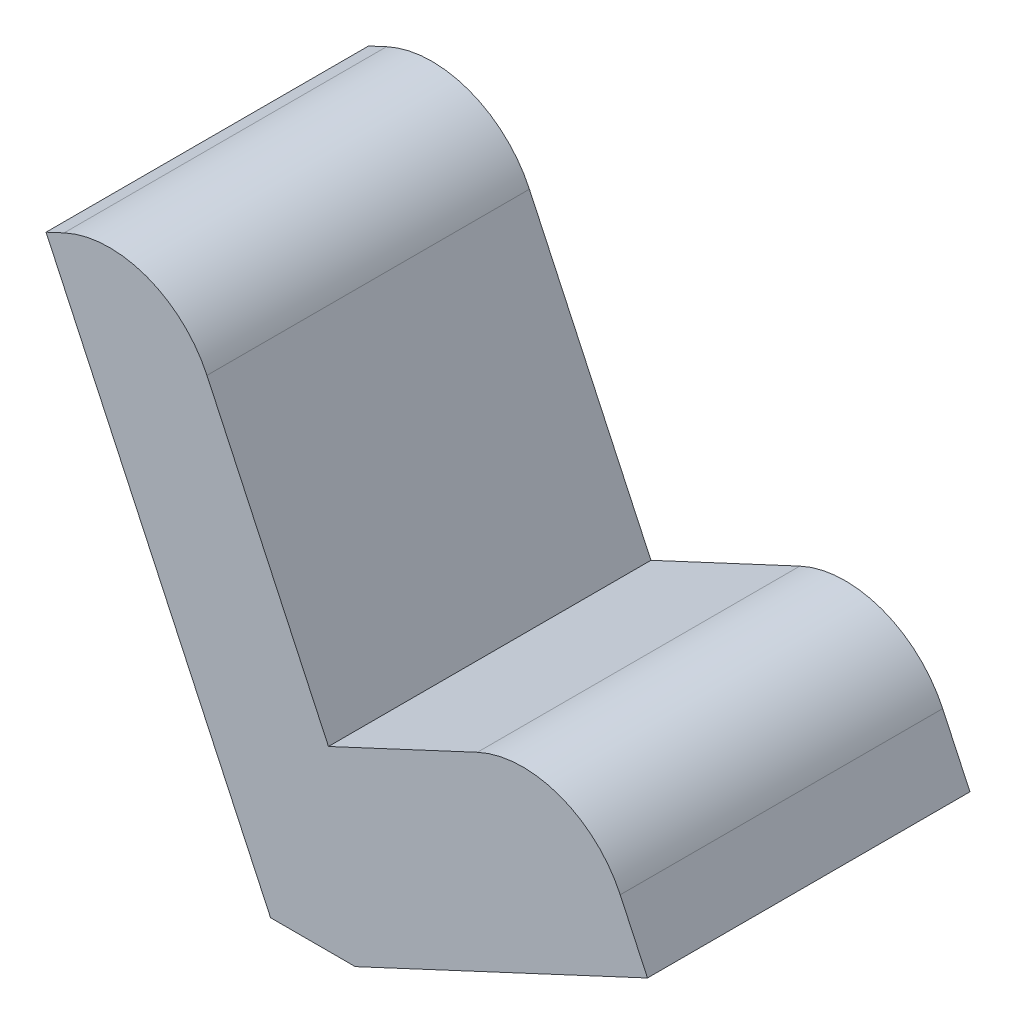
SolidWorks part; units mm, degrees
ref_plane "Front Plane" through (0, 0, 0) normal (0, 0, 1) x (1, 0, 0)
ref_plane "Top Plane" through (0, 0, 0) normal (0, 1, 0) x (1, 0, 0)
ref_plane "Right Plane" through (0, 0, 0) normal (1, 0, 0) x (0, 0, -1)
sketch "Sketch1" plane through (0, 0, 0) normal (0, 0, 1) x (1, 0, 0)
  line L0 (32.511, 16.4934) -> (46.3643, 22.9533)
  line L1 (27.1234, 0) -> (35, 0)
  line L2 (35, 0) -> (62.1892, 12.6785)
  line L3 (62.1892, 12.6785) -> (60.7824, 15.6955)
  line L4 (32.511, 16.4934) -> (21.2049, 40.7393)
  line L5 (7.9157, 45.5762) -> (6.236, 44.793)
  line L6 (6.236, 44.793) -> (27.1234, 0)
  line L7 (59.6535, 18.1164) -> (60.7824, 15.6955)
  arc A0 (46.3643, 22.9533) -> (59.6535, 18.1164) centre (50.5904, 13.8902) cw
  arc A1 (21.2049, 40.7393) -> (7.9157, 45.5762) centre (12.1419, 36.5132) ccw
  dimension "D1" = 10
  dimension "D3" = 10
  dimension "D2" = 25
  dimension "D6" = 30
extrude "Boss-Extrude1" add sketch "Sketch1" along normal blind 30
